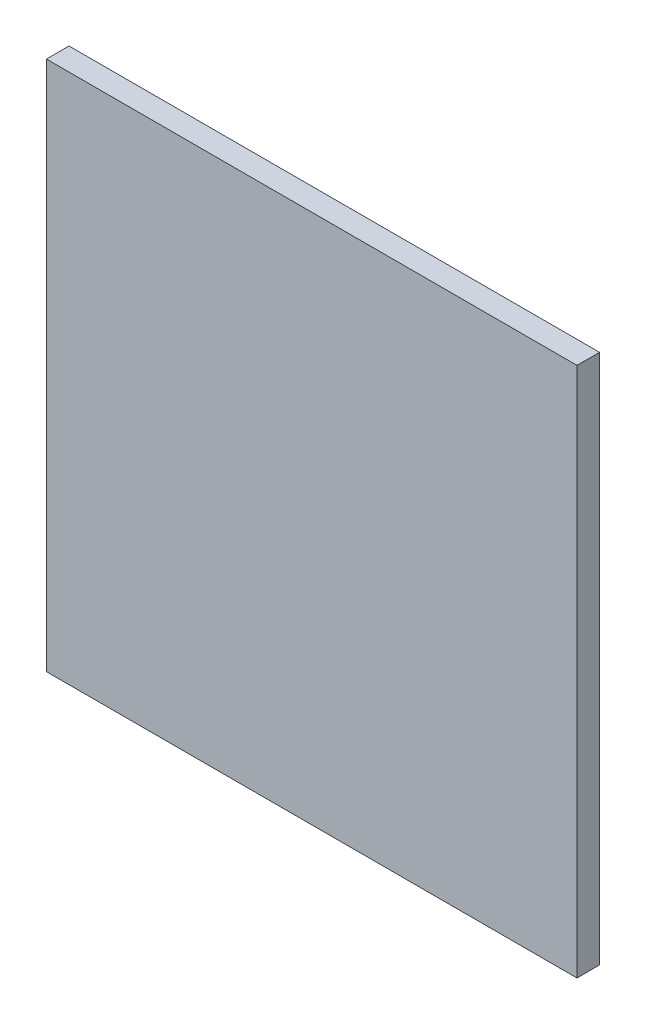
SolidWorks part; units mm, degrees
material "BUTİL"
ref_plane "Ön Düzlem" through (0, 0, 0) normal (0, 0, 1) x (1, 0, 0)
ref_plane "Üst Düzlem" through (0, 0, 0) normal (0, 1, 0) x (1, 0, 0)
ref_plane "Sağ Düzlem" through (0, 0, 0) normal (1, 0, 0) x (0, 0, -1)
sketch "Çizim1" plane through (0, 0, 0) normal (0, 0, 1) x (1, 0, 0)
  line L1 (-117.5, 117.5) -> (117.5, 117.5)
  line L2 (-117.5, 117.5) -> (-117.5, -117.5)
  line L3 (-117.5, -117.5) -> (117.5, -117.5)
  line L4 (117.5, 117.5) -> (117.5, -117.5)
  point P4 (0, 117.5)
  point P6 (-117.5, 0)
  dimension "D1" = 235
  dimension "D2" = 235
extrude "Yükseklik-Ekstrüzyon1" add sketch "Çizim1" along normal blind 10
